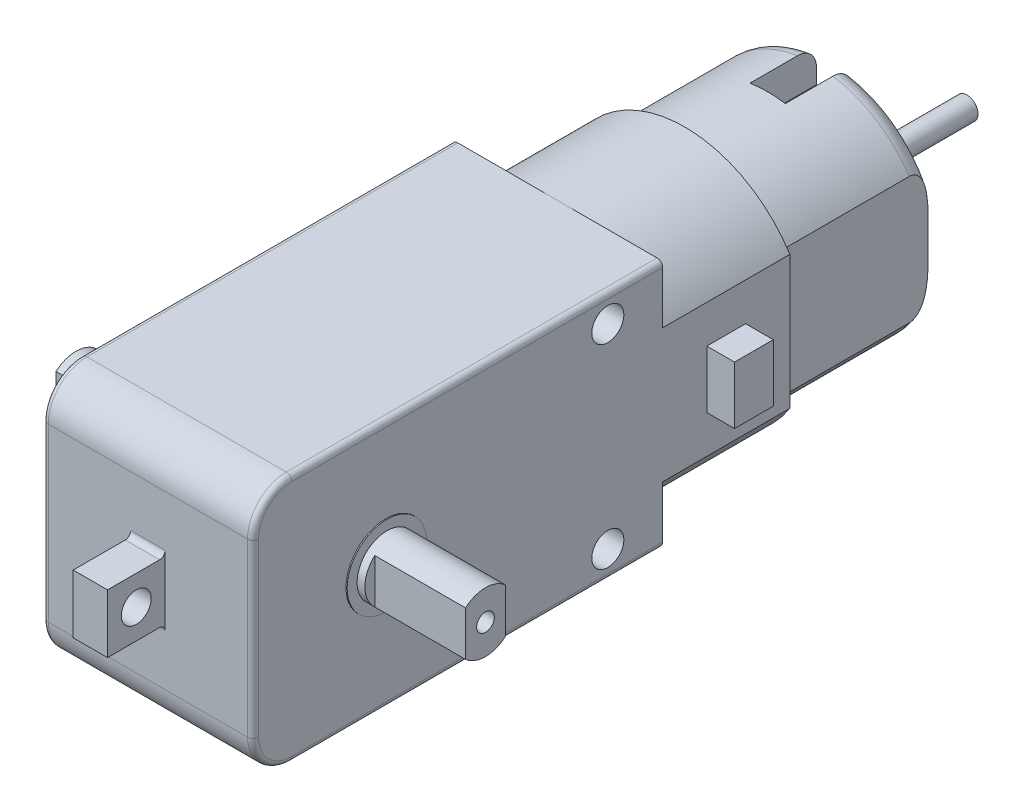
SolidWorks part; units mm, degrees
ref_plane "Front Plane" through (0, 0, 0) normal (0, 0, 1) x (1, 0, 0)
ref_plane "Top Plane" through (0, 0, 0) normal (0, 1, 0) x (1, 0, 0)
ref_plane "Right Plane" through (0, 0, 0) normal (1, 0, 0) x (0, 0, -1)
sketch "Sketch1" plane through (0, 0, 0) normal (1, 0, 0) x (0, 0, -1)
  line L0 (0, 0) -> (-38.2014, 0) construction
  line L2 (-37, -11.25) -> (0, -11.25)
  line L3 (-37, -11.25) -> (-37, 11.25)
  line L4 (-37, 11.25) -> (0, 11.25)
  line L5 (0, -11.25) -> (0, 11.25)
  line L6 (-37, -11.25) -> (0, 11.25) construction
  line L7 (-37, 11.25) -> (0, -11.25) construction
  point P3 (-18.5, 0)
  dimension "D1" = 22.5
  dimension "D2" = 37
extrude "Boss-Extrude1" add sketch "Sketch1" along normal blind 19
sketch "Sketch2" plane through (0, 0, 37) normal (0, 0, 1) x (1, 0, 0)
  line L0 (9.5, 11.25) -> (9.5, -11.25) construction
  line L1 (19, 11.25) -> (0, 11.25) construction
  line L2 (19, -11.25) -> (0, -11.25) construction
  line L3 (0, 0) -> (19, 0) construction
  line L4 (19, 11.25) -> (19, -11.25) construction
  line L6 (7.95, -2.65) -> (11.05, -2.65)
  line L7 (7.95, -2.65) -> (7.95, 2.65)
  line L8 (7.95, 2.65) -> (11.05, 2.65)
  line L9 (11.05, -2.65) -> (11.05, 2.65)
  line L10 (7.95, -2.65) -> (11.05, 2.65) construction
  line L11 (7.95, 2.65) -> (11.05, -2.65) construction
  point P11 (9.5, 0)
  dimension "D1" = 3.1
  dimension "D2" = 5.3
extrude "Boss-Extrude2" add sketch "Sketch2" along normal blind 5.2
sketch "Sketch3" plane through (11.05, 0, 0) normal (1, 0, 0) x (0, 0, -1)
  line L0 (-42.2, 2.65) -> (-37, -2.65) construction
  line L1 (-42.2, -2.65) -> (-37, 2.65) construction
  line L2 (-37, 11.25) -> (-37, -11.25) construction
  line L3 (-37, -2.65) -> (-37, 2.65) construction
  line L4 (-42.2, 2.65) -> (-37, 2.65) construction
  circle A0 centre (-39.6, 0) radius 1.35
  dimension "D1" = 2.7
extrude "Cut-Extrude1" cut sketch "Sketch3" against normal through all
fillet "Fillet1" radius 3.5 2 edges at (9.5, -11.25, 37) (9.5, 11.25, 37)
sketch "Sketch4" plane through (19, 0, 0) normal (1, 0, 0) x (0, 0, -1)
  line L0 (-25, 11.25) -> (-25, -11.25) construction
  line L1 (0, 11.25) -> (-33.5, 11.25) construction
  line L2 (-33.5, -11.25) -> (0, -11.25) construction
  line L3 (-37, 0) -> (0, 0) construction
  line L4 (-37, 7.75) -> (-37, -7.75) construction
  circle A0 centre (-25, 0) radius 3.6
  dimension "D2" = 7.2
  dimension "D1" = 12
extrude "Boss-Extrude3" add sketch "Sketch4" along normal blind 0.1
sketch "Sketch5" plane through (0, 0, 0) normal (-1, 0, 0) x (0, 0, 1)
  circle A0 centre (25, 0) radius 3.6 construction
  circle A1 centre (25, 0) radius 3.6
extrude "Boss-Extrude4" add sketch "Sketch5" along normal blind 0.1
sketch "Sketch6" plane through (19.1, 0, 0) normal (1, 0, 0) x (0, 0, -1)
  circle A0 centre (-25, 0) radius 2.7
  dimension "D1" = 5.4
extrude "Boss-Extrude5" add sketch "Sketch6" along normal blind 8.9
sketch "Sketch7" plane through (-0.1, 0, 0) normal (-1, 0, 0) x (0, 0, 1)
  circle A0 centre (25, 0) radius 2.7 construction
  circle A1 centre (25, 0) radius 2.7
extrude "Boss-Extrude6" add sketch "Sketch7" along normal blind 8.9
fillet "Fillet2" radius 0.5 2 edges at (9.5, -2.65, 37) (9.5, 2.65, 37)
sketch "Sketch8" plane through (28, 0, 0) normal (1, 0, 0) x (0, 0, -1)
  line L0 (-26.8, 2.0125) -> (-26.8, -2.0125)
  line L2 (-23.2, -2.0125) -> (-23.2, 2.0125)
  circle A0 centre (-25, 0) radius 2.7 construction
  circle A1 centre (-25, 0) radius 2.7
  circle M3 centre (-25, 0) radius 2.7
  dimension "D1" = 3.6
extrude "Cut-Extrude2" cut sketch "Sketch8" against normal blind 8.2 contours L0 M3 | L2 M3
sketch "Sketch9" plane through (-9, 0, 0) normal (-1, 0, 0) x (0, 0, 1)
  line L0 (26.8, 2.0125) -> (26.8, -2.0125) construction
  line L1 (23.2, -2.0125) -> (23.2, 2.0125) construction
  line L2 (26.8, 2.0125) -> (26.8, -2.0125)
  line L3 (23.2, -2.0125) -> (23.2, 2.0125)
  circle A0 centre (25, 0) radius 2.7 construction
  circle A1 centre (25, 0) radius 2.7
  circle M1 centre (25, 0) radius 2.7
extrude "Cut-Extrude3" cut sketch "Sketch9" against normal blind 8.2 contours L3 M1 | L2 M1
hole_wizard "M2x0.4 Tapped Hole1" positions "Sketch11" profile "Sketch10" tap size "M2x0.4" standard "ANSI Metric"
sketch "Sketch11" plane through (28, 0, 0) normal (1, 0, 0) x (0, 0, -1)
  point P0 (-25, 0)
sketch "Sketch10" plane through (28, 0, 25) normal (0, 1, 0) x (0, 0, -1)
  line L0 (0, 0) -> (0, 5.6807)
  line L1 (0, 5.6807) -> (0.8, 5.2)
  line L2 (0.8, 5.2) -> (0.8, 0)
  line L5 (0.8, 0) -> (0, 0)
  line L10 (0, 5.6807) -> (-0.8, 5.2) construction
  line L11 (0, -6.35) -> (0, 107.95) construction
  dimension "Tap Drill Dia." = 1.6
  dimension "Tap Drill Depth" = 5.2
  dimension "Drill Angle" = 118
cosmetic thread "Hole Thread1" parameters "D1"=4, "D2"=2
hole_wizard "M2x0.4 Tapped Hole2" positions "Sketch15" profile "Sketch14" tap size "M2x0.4" standard "ANSI Metric"
sketch "Sketch15" plane through (-9, 0, 0) normal (-1, 0, 0) x (0, 0, 1)
  point P0 (25, 0)
sketch "Sketch14" plane through (-9, 0, 25) normal (0, 1, 0) x (0, 0, 1)
  line L0 (0, 0) -> (0, 5.6807)
  line L1 (0, 5.6807) -> (0.8, 5.2)
  line L2 (0.8, 5.2) -> (0.8, 0)
  line L5 (0.8, 0) -> (0, 0)
  line L10 (0, 5.6807) -> (-0.8, 5.2) construction
  line L11 (0, -6.35) -> (0, 107.95) construction
  dimension "Tap Drill Dia." = 1.6
  dimension "Tap Drill Depth" = 5.2
  dimension "Drill Angle" = 118
cosmetic thread "Hole Thread2" parameters "D1"=4, "D2"=2
sketch "Sketch16" plane through (0, 0, 0) normal (-1, 0, 0) x (0, 0, 1)
  line L0 (0, 0) -> (21.4, 0) construction
  circle A0 centre (25, 0) radius 3.6 construction
  circle A1 centre (13.75, 0) radius 1.95
  circle A4 centre (25, 0) radius 3.6 construction
  dimension "D1" = 3.9
  dimension "D2" = 5.7
extrude "Boss-Extrude7" add sketch "Sketch16" along normal blind 2
sketch "Sketch17" plane through (0, 0, 0) normal (0, 0, -1) x (-1, 0, 0)
  line L0 (-19, 11.25) -> (0, -11.25) construction
  line L1 (-19, -11.25) -> (0, 11.25) construction
  line L2 (-19, -11.25) -> (-19, 11.25) construction
  line L3 (-19, -11.25) -> (-19, 11.25)
  line L6 (-1.3, -11.25) -> (-1.3, 11.25)
  line L7 (-1.3, -11.25) -> (-1.3, 11.25)
  circle A0 centre (-9.5, 0) radius 11.25
  dimension "D1" = 1.3
extrude "Boss-Extrude8" add sketch "Sketch17" along normal blind 11.5 contours L7 A0 L3
sketch "Sketch18" plane through (19, 0, 0) normal (1, 0, 0) x (0, 0, -1)
  line L0 (11.5, 0) -> (0, 0) construction
  line L1 (11.5, 6.026) -> (11.5, -6.026) construction
  line L3 (4, -2.6) -> (7.5, -2.6)
  line L4 (4, -2.6) -> (4, 2.6)
  line L5 (4, 2.6) -> (7.5, 2.6)
  line L6 (7.5, -2.6) -> (7.5, 2.6)
  line L7 (4, -2.6) -> (7.5, 2.6) construction
  line L8 (4, 2.6) -> (7.5, -2.6) construction
  point P5 (5.75, 0)
  dimension "D1" = 4
  dimension "D2" = 5.2
  dimension "D3" = 3.5
extrude "Boss-Extrude9" add sketch "Sketch18" along normal blind 2.5
sketch "Sketch19" plane through (1.3, 0, 0) normal (-1, 0, 0) x (0, 0, 1)
  line L0 (-7.5, 2.6) -> (-4, 2.6) construction
  line L1 (-4, 2.6) -> (-4, -2.6) construction
  line L2 (-4, -2.6) -> (-7.5, -2.6) construction
  line L3 (-7.5, -2.6) -> (-7.5, 2.6) construction
  line L4 (-7.5, 2.6) -> (-4, 2.6)
  line L5 (-4, 2.6) -> (-4, -2.6)
  line L6 (-4, -2.6) -> (-7.5, -2.6)
  line L7 (-7.5, -2.6) -> (-7.5, 2.6)
extrude "Boss-Extrude10" add sketch "Sketch19" along normal blind 2.5
sketch "Sketch20" plane through (0, 0, -11.5) normal (0, 0, -1) x (-1, 0, 0)
  line L20 (-18, 6.026) -> (-18, -6.026)
  line L21 (-18, 5.7282) -> (-18, -5.7282)
  line L23 (-2.3, -7.7021) -> (-2.3, 7.7021)
  line L24 (-2.3, -7.2954) -> (-2.3, 7.2954)
  arc A30 (-2.0289, 7.0175) -> (-18.1556, 5.4903) centre (-9.5, 0) ccw
  arc A31 (-2.3, 7.2954) -> (-18, 5.7282) centre (-9.5, 0) ccw
  arc A34 (-18.1556, -5.4903) -> (-2.0289, -7.0175) centre (-9.5, 0) ccw
  arc A35 (-18, -5.7282) -> (-2.3, -7.2954) centre (-9.5, 0) ccw
  dimension "D1" = 1
  dimension "D2" = 1
  dimension "D3" = 1
  dimension "D4" = 1
extrude "Boss-Extrude11" add sketch "Sketch20" along normal blind 13.5
fillet "Fillet3" radius 1.7 2 edges at (10.5181, -10.1993, -25) (10.5181, 10.1993, -25)
sketch "Sketch21" plane through (0, 0, -25) normal (0, 0, -1) x (-1, 0, 0)
  line L0 (-5.5, 3) -> (-5.5, -3)
  circle A0 centre (-9.5, 0) radius 5
  dimension "D1" = 10
  dimension "D2" = 9
extrude "Boss-Extrude12" add sketch "Sketch21" along normal blind 2 contours L0 A0
sketch "Sketch23" plane through (0, 0, -25) normal (0, 0, -1) x (-1, 0, 0)
  line L0 (-9.5, 10.25) -> (-9.5, -11.25) construction
  line L1 (-7.9, 7) -> (-7.9, -7) construction
  line L2 (-11.1, 13.5) -> (-7.9, 13.5)
  line L3 (-11.1, 13.5) -> (-11.1, 7)
  line L4 (-11.1, 7) -> (-7.9, 7)
  line L5 (-7.9, 13.5) -> (-7.9, 7)
  line L6 (-11.1, 13.5) -> (-7.9, 7) construction
  line L7 (-11.1, 7) -> (-7.9, 13.5) construction
  line L8 (-11.1, -15.5) -> (-7.9, -15.5)
  line L9 (-11.1, -15.5) -> (-11.1, -7)
  line L10 (-11.1, -7) -> (-7.9, -7)
  line L11 (-7.9, -15.5) -> (-7.9, -7)
  line L12 (-11.1, -15.5) -> (-7.9, -7) construction
  line L13 (-11.1, -7) -> (-7.9, -15.5) construction
  line L14 (-9.5, 0) -> (-7.9, 7) construction
  line L16 (-9.5, 0) -> (-7.9, -7) construction
  arc A0 (-2.3, 7.2954) -> (-18, 5.7282) centre (-9.5, 0) ccw construction
  arc A1 (-2.3, 4.6111) -> (-18, 0.9233) centre (-9.5, 0) ccw construction
  arc A2 (-2.3, 4.6111) -> (-18, 0.9233) centre (-9.5, 0) ccw construction
  point P15 (0, 0)
  point P16 (0, 0)
  point P18 (0, 0)
  point P22 (-9.5, -0.5)
  dimension "D1" = 14
  dimension "D2" = 3.2
extrude "Cut-Extrude4" cut sketch "Sketch23" against normal blind 6
sketch "Sketch24" plane through (0, -11.25, 0) normal (0, -1, 0) x (1, 0, 0)
  line L0 (19, 25) -> (0, 25) construction
  line L1 (19, 33.5) -> (19, 0) construction
  line L2 (0, 33.5) -> (0, 0) construction
  line L3 (28, 25) -> (19, 25) construction
  line L4 (28, 23.2) -> (28, 26.8) construction
ref_plane "Plane1" through (0, 0, 25) normal (0, 0, 1) x (-1, 0, 0)
sketch "Sketch25" plane through (19, 0, 0) normal (1, 0, 0) x (0, 0, -1)
  line L0 (-4.95, 11.25) -> (-4.95, -11.25) construction
  line L1 (0, 11.25) -> (-33.5, 11.25) construction
  line L2 (-33.5, -11.25) -> (0, -11.25) construction
  line L4 (0, 6.026) -> (0, 11.25) construction
  line L5 (-37, 7.75) -> (-37, -7.75) construction
  circle A0 centre (-4.95, 8.8) radius 1.45
  circle A1 centre (-4.95, -8.8) radius 1.45
  dimension "D1" = 2.9
  dimension "D2" = 14.7
  dimension "D5" = 3.5
  dimension "D3" = 1
  dimension "D4" = 1
  dimension "D6" = 30.6
extrude "Cut-Extrude5" cut sketch "Sketch25" against normal through all
fillet "Fillet4" radius 0.5 10 edges at (0, -11.25, 16.75) (0, -10.2249, 35.9749) (0, 0, 37) (0, 10.2249, 35.9749) (19, -11.25, 16.75) (19, -10.2249, 35.9749) (19, 0, 37) (19, 10.2249, 35.9749) (0, 11.25, 16.75) (19, 11.25, 16.75)
sketch "Sketch26" plane through (0, 0, -27) normal (0, 0, -1) x (-1, 0, 0)
  circle A0 centre (-9.5, 0) radius 1
  dimension "D1" = 2
extrude "Boss-Extrude13" add sketch "Sketch26" along normal blind 10
